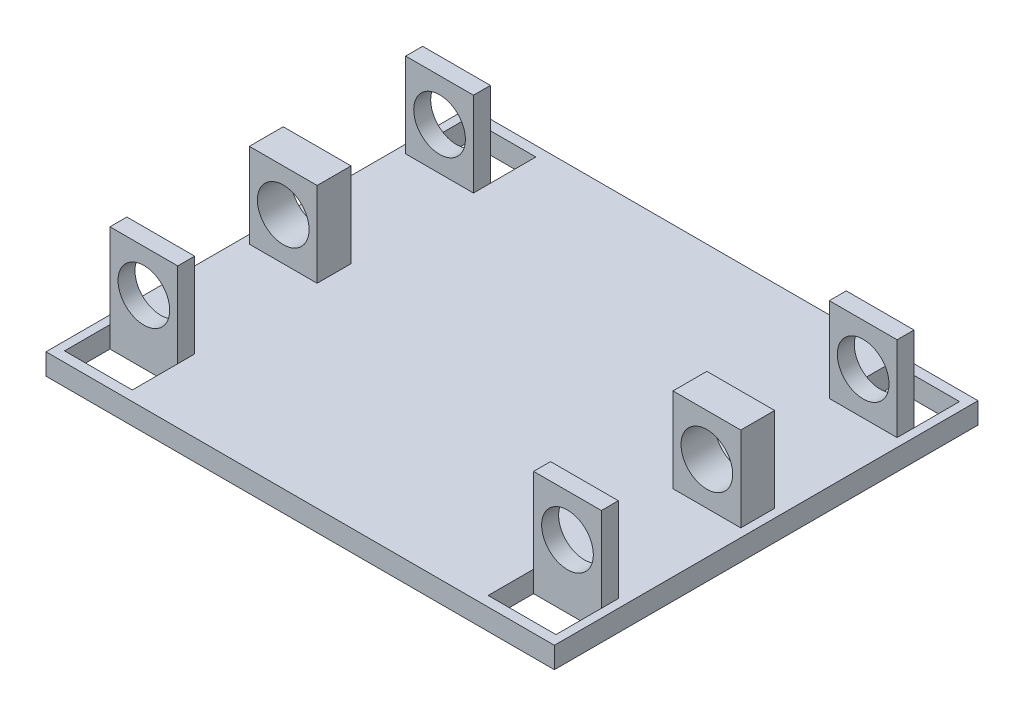
SolidWorks part; units mm, degrees
ref_plane "Front Plane" through (0, 0, 0) normal (0, 0, 1) x (1, 0, 0)
ref_plane "Top Plane" through (0, 0, 0) normal (0, 1, 0) x (1, 0, 0)
ref_plane "Right Plane" through (0, 0, 0) normal (1, 0, 0) x (0, 0, -1)
sketch "Sketch1" plane through (0, 0, 0) normal (0, 1, 0) x (1, 0, 0)
  line L1 (-30, -25) -> (30, -25)
  line L2 (-30, -25) -> (-30, 25)
  line L3 (-30, 25) -> (30, 25)
  line L4 (30, -25) -> (30, 25)
  line L5 (-30, -25) -> (30, 25) construction
  line L6 (-30, 25) -> (30, -25) construction
  point P0 (0, 0)
  dimension "D1" = 60
  dimension "D2" = 50
extrude "Boss-Extrude1" add sketch "Sketch1" along normal blind 2.5
sketch "Sketch2" plane through (0, 2.5, 0) normal (0, 1, 0) x (1, 0, 0)
  line L0 (-30, -1) -> (-20, -1) construction
  line L1 (-30, 25) -> (-30, -25) construction
  line L2 (-20, -1) -> (-20, -25) construction
  line L3 (-30, -25) -> (30, -25) construction
  line L5 (-29, 0) -> (-21, 0)
  line L6 (-29, 0) -> (-29, -2)
  line L7 (-29, -2) -> (-21, -2)
  line L8 (-21, 0) -> (-21, -2)
  line L9 (-29, 0) -> (-21, -2) construction
  line L10 (-29, -2) -> (-21, 0) construction
  point P7 (-25, -1)
  dimension "D1" = 10
  dimension "D2" = 24
  dimension "D3" = 8
  dimension "D4" = 2
extrude "Boss-Extrude2" add sketch "Sketch2" along normal blind 10
sketch "Sketch3" plane through (0, 0, 2) normal (0, 0, 1) x (1, 0, 0)
  line L0 (-29, 2.5) -> (-21, 12.5) construction
  circle A0 centre (-25, 7.5) radius 3.05
extrude "Cut-Extrude1" cut sketch "Sketch3" against normal up to next
sketch "Sketch4" plane through (0, 2.5, 0) normal (0, 1, 0) x (1, 0, 0)
  line L0 (-30, 1) -> (-20, 1) construction
  line L1 (-30, 25) -> (-30, -25) construction
  line L2 (-20, 1) -> (-20, 25) construction
  line L3 (30, 25) -> (-30, 25) construction
  line L5 (-29, 2) -> (-21, 2)
  line L6 (-29, 2) -> (-29, 0)
  line L7 (-29, 0) -> (-21, 0)
  line L8 (-21, 2) -> (-21, 0)
  line L9 (-29, 2) -> (-21, 0) construction
  line L10 (-29, 0) -> (-21, 2) construction
  point P4 (-25, 1)
  dimension "D1" = 24
  dimension "D2" = 10
extrude "Boss-Extrude3" add sketch "Sketch4" along normal blind 10
sketch "Sketch6" plane through (0, 0, -2) normal (0, 0, -1) x (-1, 0, 0)
  line L0 (21, 2.5) -> (29, 12.5) construction
  circle A0 centre (25, 7.5) radius 3.05
extrude "Cut-Extrude2" cut sketch "Sketch6" against normal up to next
sketch "Sketch7" plane through (0, 2.5, 0) normal (0, 1, 0) x (1, 0, 0)
  line L0 (20, 25) -> (20, 0) construction
  line L1 (30, 25) -> (-30, 25) construction
  line L2 (20, 0) -> (30, 0) construction
  line L3 (30, -25) -> (30, 25) construction
  line L5 (29, -2) -> (21, -2)
  line L6 (29, -2) -> (29, 2)
  line L7 (29, 2) -> (21, 2)
  line L8 (21, -2) -> (21, 2)
  line L9 (29, -2) -> (21, 2) construction
  line L10 (29, 2) -> (21, -2) construction
  point P4 (25, 0)
  dimension "D1" = 25
  dimension "D2" = 10
  dimension "D3" = 4
  dimension "D4" = 8
extrude "Boss-Extrude4" add sketch "Sketch7" along normal blind 10
sketch "Sketch8" plane through (0, 0, 2) normal (0, 0, 1) x (1, 0, 0)
  line L0 (21, 2.5) -> (29, 12.5) construction
  circle A0 centre (25, 7.5) radius 3.05
extrude "Cut-Extrude3" cut sketch "Sketch8" against normal up to next
sketch "Sketch9" plane through (0, 2.5, 0) normal (0, 1, 0) x (1, 0, 0)
  line L0 (-25, -2) -> (-25, 17.4507) construction
  line L1 (-29, -2) -> (-21, -2) construction
  line L2 (-25, 17.4507) -> (-30, 17.4507) construction
  line L3 (-30, 25) -> (-30, -25) construction
  line L4 (-30, 0) -> (30, 0) construction
  line L5 (-29, 18.4507) -> (-21, 18.4507)
  line L6 (-29, 18.4507) -> (-29, 16.4507)
  line L7 (-29, 16.4507) -> (-21, 16.4507)
  line L8 (-21, 18.4507) -> (-21, 16.4507)
  line L9 (-29, 18.4507) -> (-21, 16.4507) construction
  line L10 (-29, 16.4507) -> (-21, 18.4507) construction
  line L11 (30, -25) -> (30, 25) construction
  line L12 (0, 25) -> (0, -25) construction
  line L13 (30, 25) -> (-30, 25) construction
  line L14 (-30, -25) -> (30, -25) construction
  line L15 (-29, -16.4507) -> (-21, -18.4507) construction
  line L16 (-29, -18.4507) -> (-21, -16.4507) construction
  line L17 (-25, -17.4507) -> (-30, -17.4507) construction
  line L18 (-25, 2) -> (-25, -17.4507) construction
  line L19 (-21, -18.4507) -> (-21, -16.4507)
  line L20 (-29, -16.4507) -> (-21, -16.4507)
  line L21 (-29, -18.4507) -> (-29, -16.4507)
  line L22 (-29, -18.4507) -> (-21, -18.4507)
  line L23 (25, 2) -> (25, -17.4507) construction
  line L24 (25, -17.4507) -> (30, -17.4507) construction
  line L25 (29, -18.4507) -> (21, -16.4507) construction
  line L26 (29, -16.4507) -> (21, -18.4507) construction
  line L27 (29, -18.4507) -> (21, -18.4507)
  line L28 (29, -18.4507) -> (29, -16.4507)
  line L29 (29, -16.4507) -> (21, -16.4507)
  line L30 (21, -18.4507) -> (21, -16.4507)
  line L31 (29, 16.4507) -> (21, 18.4507) construction
  line L32 (29, 18.4507) -> (21, 16.4507) construction
  line L33 (21, 18.4507) -> (21, 16.4507)
  line L34 (29, 16.4507) -> (21, 16.4507)
  line L35 (29, 18.4507) -> (29, 16.4507)
  line L36 (29, 18.4507) -> (21, 18.4507)
  dimension "D1" = 8
  dimension "D2" = 2
extrude "Boss-Extrude5" add sketch "Sketch9" along normal blind 10
sketch "Sketch10" plane through (0, 0, -18.4507) normal (0, 0, -1) x (-1, 0, 0)
  line L0 (21, 2.5) -> (29, 12.5) construction
  circle A0 centre (25, 7.5) radius 3.05
extrude "Cut-Extrude4" cut sketch "Sketch10" against normal up to next
sketch "Sketch12" plane through (0, 0, 18.4507) normal (0, 0, 1) x (1, 0, 0)
  line L0 (-29, 2.5) -> (-21, 12.5) construction
  circle A0 centre (-25, 7.5) radius 3.05
extrude "Cut-Extrude5" cut sketch "Sketch12" against normal up to next
sketch "Sketch13" plane through (0, 0, -18.4507) normal (0, 0, -1) x (-1, 0, 0)
  line L0 (-29, 2.5) -> (-21, 12.5) construction
  circle A0 centre (-25, 7.5) radius 3.05
extrude "Cut-Extrude6" cut sketch "Sketch13" against normal up to next
sketch "Sketch14" plane through (0, 0, 18.4507) normal (0, 0, 1) x (1, 0, 0)
  line L0 (21, 2.5) -> (29, 12.5) construction
  circle A0 centre (25, 7.5) radius 3.05
extrude "Cut-Extrude7" cut sketch "Sketch14" against normal up to next
sketch "Sketch15" plane through (0, 2.5, 0) normal (0, 1, 0) x (1, 0, 0)
  line L0 (-25, 18.4507) -> (-25, 22.4507) construction
  line L1 (-21, 18.4507) -> (-29, 18.4507) construction
  line L2 (-25, 22.4507) -> (-28.1, 22.4507) construction
  line L3 (0, 25) -> (0, -25) construction
  line L4 (-30, 0) -> (30, 0) construction
  line L5 (-29, 18.4507) -> (-21, 18.4507)
  line L6 (-29, 18.4507) -> (-29, 23.8155)
  line L7 (-29, 23.8155) -> (-21, 23.8155)
  line L8 (-21, 18.4507) -> (-21, 23.8155)
  line L9 (-30, 25) -> (-30, -25) construction
  line L10 (30, -25) -> (30, 25) construction
  line L11 (30, 25) -> (-30, 25) construction
  line L12 (-30, -25) -> (30, -25) construction
  line L13 (29, 23.8155) -> (21, 23.8155)
  line L14 (21, 18.4507) -> (21, 23.8155)
  line L15 (29, 18.4507) -> (21, 18.4507)
  line L16 (29, 18.4507) -> (29, 23.8155)
  line L17 (-29, -18.4507) -> (-21, -18.4507)
  line L18 (-29, -18.4507) -> (-29, -23.8155)
  line L19 (-29, -23.8155) -> (-21, -23.8155)
  line L20 (-21, -18.4507) -> (-21, -23.8155)
  line L21 (21, -18.4507) -> (21, -23.8155)
  line L22 (29, -23.8155) -> (21, -23.8155)
  line L23 (29, -18.4507) -> (29, -23.8155)
  line L24 (29, -18.4507) -> (21, -18.4507)
  dimension "D1" = 4
extrude "Cut-Extrude8" cut sketch "Sketch15" against normal up to next
sketch "Sketch16" plane through (0, 2.5, 0) normal (0, 1, 0) x (1, 0, 0)
  line L0 (-30, 25) -> (-30, -25) construction
  line L1 (-29, -18.4507) -> (-30, -18.4507)
  line L2 (-29, -18.4507) -> (-29, -23.8155)
  line L3 (-29, -23.8155) -> (-30, -23.8155)
  line L4 (-30, -18.4507) -> (-30, -23.8155)
  line L5 (-30, 0) -> (0, 0) construction
  line L6 (0, 0) -> (0, 25) construction
  line L7 (30, 25) -> (-30, 25) construction
  line L8 (-29, 23.8155) -> (-30, 23.8155)
  line L9 (-29, 18.4507) -> (-30, 18.4507)
  line L10 (-30, 18.4507) -> (-30, 23.8155)
  line L11 (-29, 18.4507) -> (-29, 23.8155)
